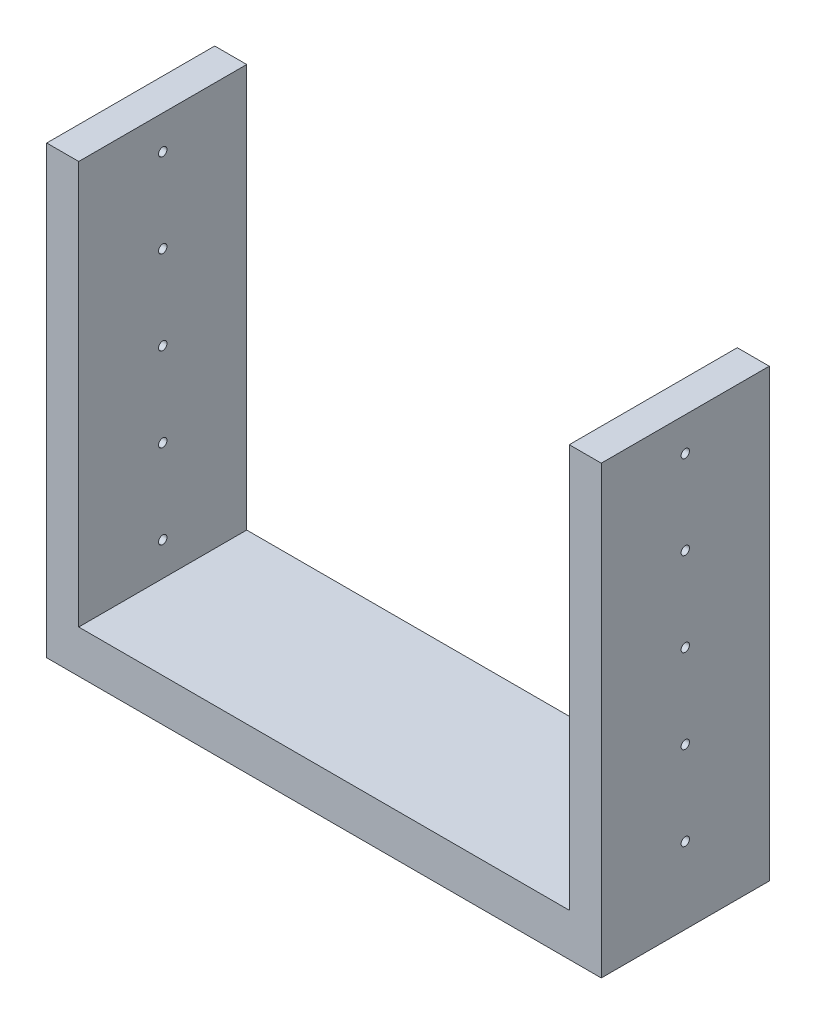
SolidWorks part; units mm, degrees
ref_plane "Front Plane" through (0, 0, 0) normal (0, 0, 1) x (1, 0, 0)
ref_plane "Top Plane" through (0, 0, 0) normal (0, 1, 0) x (1, 0, 0)
ref_plane "Right Plane" through (0, 0, 0) normal (1, 0, 0) x (0, 0, -1)
sketch "Sketch1" plane through (0, 0, 0) normal (0, 1, 0) x (1, 0, 0)
  line L1 (-78, -25) -> (78, -25)
  line L2 (-78, -25) -> (-78, 25)
  line L3 (-78, 25) -> (78, 25)
  line L4 (78, -25) -> (78, 25)
  line L5 (-78, -25) -> (78, 25) construction
  line L6 (-78, 25) -> (78, -25) construction
  point P0 (0, 0)
  dimension "D1" = 50
  dimension "D2" = 156
extrude "Boss-Extrude1" add sketch "Sketch1" along normal blind 12.7
sketch "Sketch2" plane through (0, 12.7, 0) normal (0, 1, 0) x (1, 0, 0)
  line L1 (-82.525, 25) -> (-73, 25)
  line L2 (-82.525, 25) -> (-82.525, -25)
  line L3 (-82.525, -25) -> (-73, -25)
  line L4 (-73, 25) -> (-73, -25)
  line L5 (0, 9.75) -> (0, -9.75) construction
  line L6 (73, 25) -> (73, -25)
  line L7 (82.525, -25) -> (73, -25)
  line L8 (82.525, 25) -> (82.525, -25)
  line L9 (82.525, 25) -> (73, 25)
  line L10 (78, 25) -> (-78, 25) construction
  line L11 (0, 0) -> (-71.3191, 0) construction
  dimension "D1" = 9.525
  dimension "D3" = 73
extrude "Boss-Extrude2" add sketch "Sketch2" along normal blind 120 and the other way up to surface other way up to face at (0, 0, 0)
sketch "Sketch3" plane through (82.525, 0, 0) normal (1, 0, 0) x (0, 0, -1)
  line L0 (0, 0) -> (0, 125.7507) construction
  line L1 (-25, 132.7) -> (25, 132.7) construction
  line L2 (-25, 132.7) -> (25, 132.7) construction
  line L7 (0, -25) -> (0, 100.7507) construction
  line L8 (0, -50) -> (0, 75.7507) construction
  line L9 (0, -75) -> (0, 50.7507) construction
  line L10 (0, -100) -> (0, 25.7507) construction
  circle A0 centre (0, 122.7) radius 1.25
  circle A1 centre (0, 97.7) radius 1.25
  circle A2 centre (0, 72.7) radius 1.25
  circle A3 centre (0, 47.7) radius 1.25
  circle A4 centre (0, 22.7) radius 1.25
  dimension "D1" = 2.5
  dimension "D2" = 10
  dimension "D4" = 25
  dimension "D3" = 5
extrude "Cut-Extrude1" cut sketch "Sketch3" against normal through all
equation "\"D3@Sketch2\"=60+13"
equation "\"D2@Sketch1\"=146+10"
